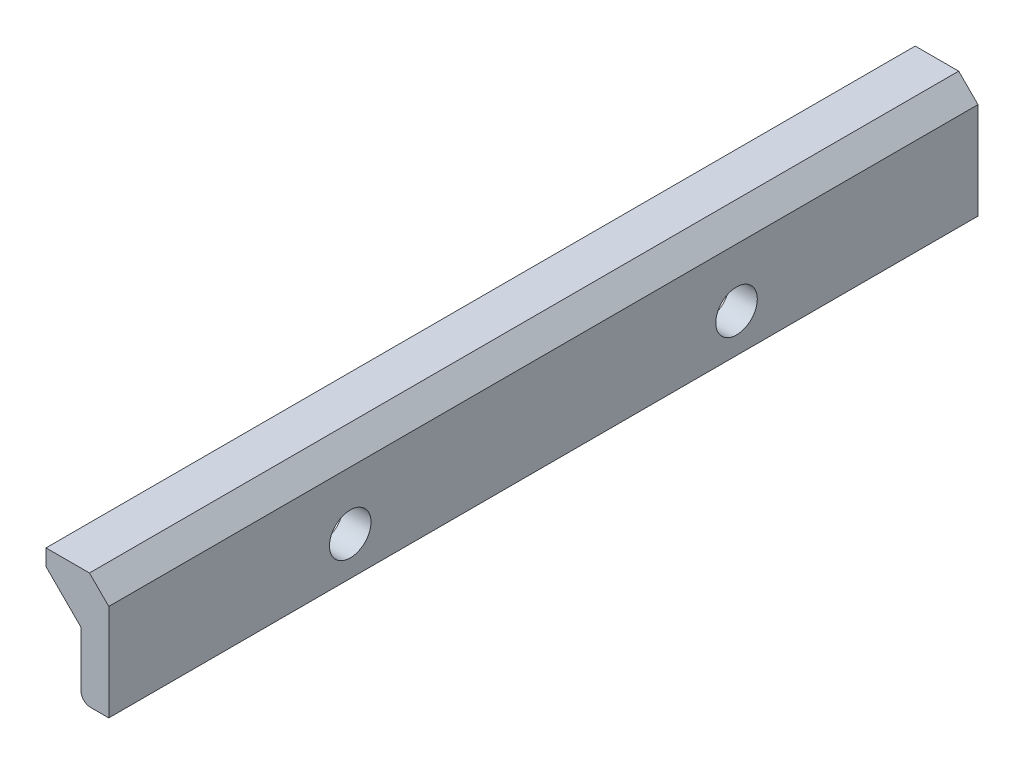
SolidWorks part; units mm, degrees
ref_plane "Płaszczyzna przednia" through (0, 0, 0) normal (0, 0, 1) x (1, 0, 0)
ref_plane "Płaszczyzna górna" through (0, 0, 0) normal (0, 1, 0) x (1, 0, 0)
ref_plane "Płaszczyzna prawa" through (0, 0, 0) normal (1, 0, 0) x (0, 0, -1)
sketch "Sketch3" plane through (0, 0, 0) normal (0, 0, 1) x (1, 0, 0)
  line L16 (3.6172, -12) -> (3.6172, -5.2972)
  line L17 (3.6172, -5.2972) -> (0, -1.68)
  line L18 (3.6172, -12) -> (6.5, -12)
  line L20 (6.5, -12) -> (6.5, -2)
  line L21 (6.5, -2) -> (4.5, 0)
  line L22 (4.5, 0) -> (0, 0)
  line L24 (0, 0) -> (0, -1.68)
  dimension "D2" = 10
  dimension "D3" = 1.68
  dimension "D4" = 6.5
  dimension "D5" = 2
  dimension "D6" = 6.7028
  dimension "D1" = 2.8828
  dimension "D7" = 135
extrude "Boss-Extrude1" add sketch "Sketch3" along normal blind 90
sketch "Sketch4" plane through (6.5, 0, 0) normal (1, 0, 0) x (0, 0, -1)
  line L0 (-90, -12) -> (0, -12) construction
  line L1 (-90, -12) -> (-90, -2) construction
  circle A0 centre (-65, -8) radius 2.15
  circle A1 centre (-25, -8) radius 2.15
  dimension "D1" = 4.3
  dimension "D2" = 4
  dimension "D3" = 40
  dimension "D4" = 25
extrude "Cut-Extrude1" cut sketch "Sketch4" against normal up to next
fillet "Fillet1" radius 1 1 edges at (3.6172, -12, 45)
